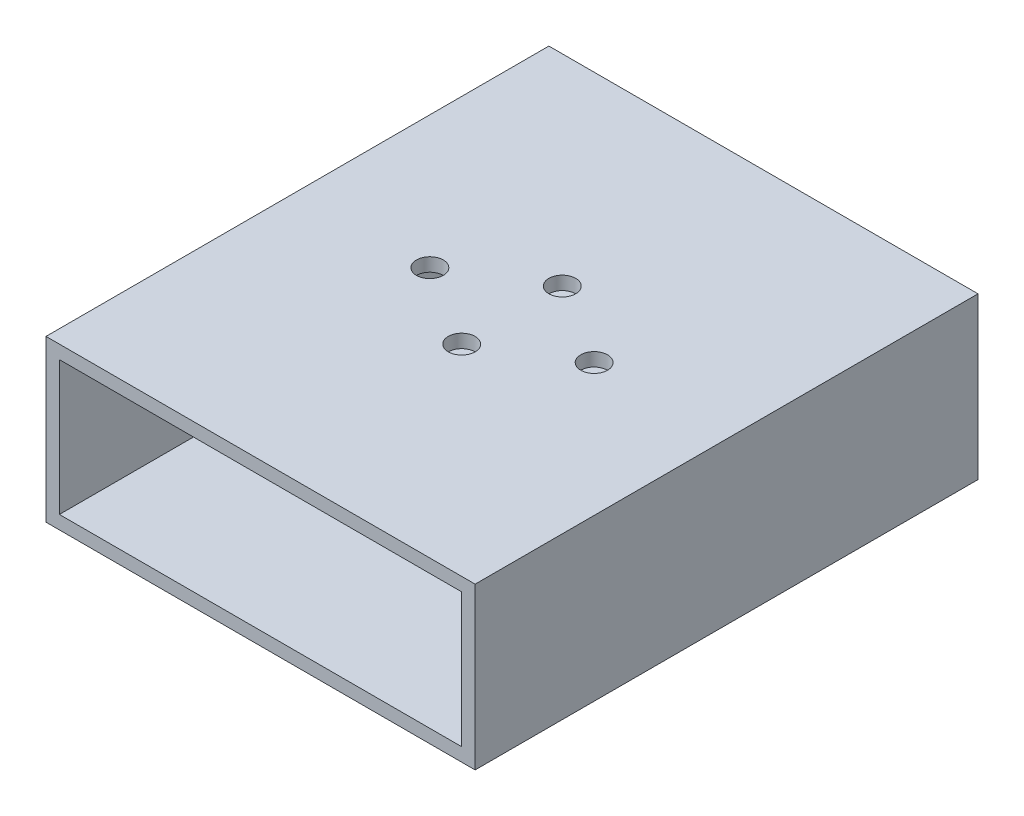
SolidWorks part; units mm, degrees
ref_plane "Ön Düzlem" through (0, 0, 0) normal (0, 0, 1) x (1, 0, 0)
ref_plane "Üst Düzlem" through (0, 0, 0) normal (0, 1, 0) x (1, 0, 0)
ref_plane "Sağ Düzlem" through (0, 0, 0) normal (1, 0, 0) x (0, 0, -1)
sketch "Çizim1" plane through (0, 0, 0) normal (0, 0, 1) x (1, 0, 0)
  line L1 (0, 0) -> (-120, 0)
  line L2 (0, 0) -> (0, 40)
  line L3 (0, 40) -> (-120, 40)
  line L4 (-120, 0) -> (-120, 40)
  dimension "D1" = 40
  dimension "D2" = 120
extrude "Ekstrüzyon-İnce1" add sketch "Çizim1" along normal blind 150 thin thin type one direction wall 4
sketch "Çizim2" plane through (0, 44, 0) normal (0, 1, 0) x (1, 0, 0)
  line L3 (-60, -75) -> (-60, -53.004) construction
  circle A0 centre (-84.5, -75) radius 4
  circle A1 centre (-35.5, -75) radius 4
  circle A2 centre (-60, -60) radius 4
  circle A3 centre (-60, -90) radius 4
  dimension "D1" = 8
  dimension "D3" = 8
extrude "Kes-Ekstrüzyon1" cut sketch "Çizim2" against normal up to next
